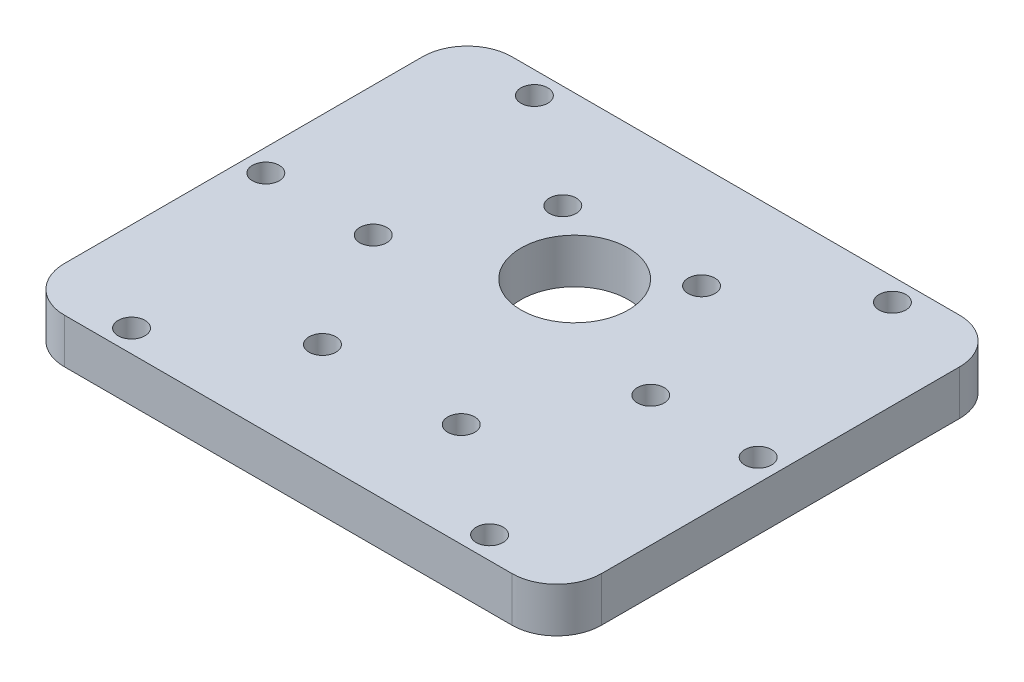
SolidWorks part; units mm, degrees
ref_plane "Front Plane" through (0, 0, 0) normal (0, 0, 1) x (1, 0, 0)
ref_plane "Top Plane" through (0, 0, 0) normal (0, 1, 0) x (1, 0, 0)
ref_plane "Right Plane" through (0, 0, 0) normal (1, 0, 0) x (0, 0, -1)
sketch "Sketch1" plane through (0, 0, 0) normal (0, 1, 0) x (1, 0, 0)
  line L1 (-30, 25) -> (30, 25)
  line L2 (-30, 25) -> (-30, -25)
  line L3 (-30, -25) -> (30, -25)
  line L4 (30, 25) -> (30, -25)
  line L5 (-30, 25) -> (30, -25) construction
  line L6 (-30, -25) -> (30, 25) construction
  point P0 (0, 0)
  dimension "D1" = 60
  dimension "D2" = 50
extrude "Boss-Extrude1" add sketch "Sketch1" along normal blind 5
sketch "Sketch2" plane through (0, 5, 0) normal (0, 1, 0) x (1, 0, 0)
  line L0 (-30, 25) -> (-30, -25) construction
  line L1 (30, -25) -> (30, 25) construction
  line L2 (30, 25) -> (-30, 25) construction
  line L7 (-15.5, 0) -> (15.5, 0) construction
  line L8 (-30, -25) -> (30, -25) construction
  line L9 (-30, 0) -> (30, 0) construction
  line L10 (-7.75, 13.4234) -> (7.75, -13.4234) construction
  line L11 (7.75, 13.4234) -> (-7.75, -13.4234) construction
  line L12 (0, 25) -> (0, -25) construction
  circle A2 centre (0, 7) radius 6
  circle A4 centre (0, 0) radius 15.5 construction
  circle A5 centre (-7.75, 13.4234) radius 1.5
  circle A6 centre (-15.5, 0) radius 1.5
  circle A7 centre (-7.75, -13.4234) radius 1.5
  circle A8 centre (7.75, -13.4234) radius 1.5
  circle A9 centre (15.5, 0) radius 1.5
  circle A10 centre (7.75, 13.4234) radius 1.5
  circle A11 centre (-20, 22.5) radius 1.5
  circle A12 centre (20, 22.5) radius 1.5
  circle A13 centre (20, -22.5) radius 1.5
  circle A14 centre (-20, -22.5) radius 1.5
  circle A15 centre (-27.5, 0) radius 1.5
  circle A16 centre (27.5, 0) radius 1.5
  point P0 (0, 0)
  dimension "D1" = 120
  dimension "D3" = 7
  dimension "D4" = 12
  dimension "D5" = 31
  dimension "D6" = 3
  dimension "D2" = 120
  dimension "D7" = 10
  dimension "D8" = 10
  dimension "D9" = 10
  dimension "D10" = 10
  dimension "D11" = 2.5
  dimension "D12" = 2.5
  dimension "D13" = 2.5
  dimension "D14" = 2.5
extrude "Cut-Extrude1" cut sketch "Sketch2" against normal blind 5
fillet "Fillet1" radius 5 4 edges at (-30, 2.5, 25) (30, 2.5, 25) (30, 2.5, -25) (-30, 2.5, -25)
